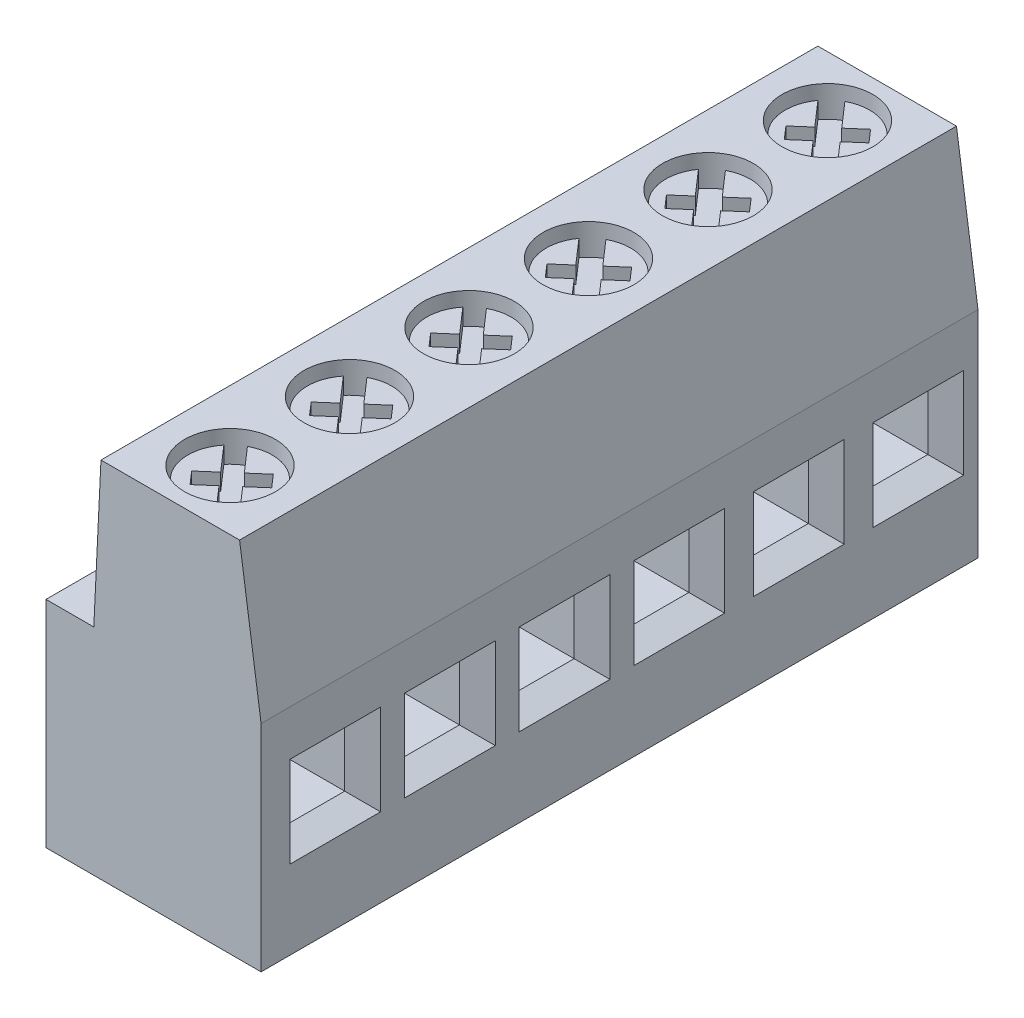
SolidWorks part; units mm, degrees
ref_plane "Front Plane" through (0, 0, 0) normal (0, 0, 1) x (1, 0, 0)
ref_plane "Top Plane" through (0, 0, 0) normal (0, 1, 0) x (1, 0, 0)
ref_plane "Right Plane" through (0, 0, 0) normal (1, 0, 0) x (0, 0, -1)
ref_plane "Plane1" through (0, 0, -15) normal (0, 0, -1) x (-1, 0, 0)
sketch "Sketch1" plane through (0, 0, -15) normal (0, 0, -1) x (-1, 0, 0)
  line L0 (-9, 0) -> (0, 0)
  line L1 (0, 0) -> (0, 15.2)
  line L2 (0, 15.2) -> (-8.1, 15.2)
  line L3 (-8.1, 15.2) -> (-9, 9)
  line L4 (-9, 9) -> (-9, 0)
extrude "Boss-Extrude1" add sketch "Sketch1" against normal blind 30
hole_wizard "Ø3.8 (3.8) Diameter Hole1" positions "Sketch3" profile "Sketch2" hole size "Ø3.8" standard "ANSI Metric"
sketch "Sketch3" plane through (0, 15.2, 0) normal (0, 1, 0) x (1, 0, 0)
  point P0 (5.2, 7.5)
sketch "Sketch2" plane through (5.2, 15.2, -7.5) normal (1, 0, 0) x (0, 0, 1)
  line L0 (0, 0) -> (0, 8)
  line L1 (0, 8) -> (1.9, 8)
  line L2 (1.9, 8) -> (1.9, 0)
  line L5 (1.9, 0) -> (0, 0)
  line L10 (0, 8) -> (-1.9, 8) construction
  line L11 (0, -6.35) -> (0, 107.95) construction
  dimension "Hole Dia." = 3.8
  dimension "Hole Depth" = 8
  dimension "Drill Angle" = 180
sketch "Sketch4" plane through (0, 7.2, 0) normal (0, 1, 0) x (-1, 0, 0)
  circle A0 centre (-5.2, -7.5) radius 1.766
extrude "Boss-Extrude2" add sketch "Sketch4" along normal blind 7.5
sketch "Sketch5" plane through (0, 14.7, 0) normal (0, 1, 0) x (-1, 0, 0)
  line L0 (-3.7681, -8.5335) -> (-6.029, -5.9407)
  arc A0 (-6.029, -5.9407) -> (-3.7681, -8.5335) centre (-5.2, -7.5) ccw
extrude "Cut-Extrude1" cut sketch "Sketch5" against normal blind 0.7
sketch "Sketch6" plane through (6.3675, 0, -5.5525) normal (0.7537, 0, -0.6572) x (-0.6572, 0, -0.7537)
  line L0 (2.5852, 14) -> (2.5852, 14.7)
  line L1 (2.5852, 14.7) -> (1.8852, 14.7)
  line L2 (1.8852, 14.7) -> (1.8852, 14)
  line L3 (1.8852, 14) -> (2.5852, 14)
extrude "Cut-Extrude2" cut sketch "Sketch6" against normal blind 0.8558
sketch "Sketch7" plane through (0, 14, 0) normal (0, 1, 0) x (-1, 0, 0)
  line L0 (-6.6319, -6.4665) -> (-4.371, -9.0593)
  arc A0 (-4.371, -9.0593) -> (-6.6319, -6.4665) centre (-5.2, -7.5) cw
extrude "Boss-Extrude3" add sketch "Sketch7" along normal blind 0.7
sketch "Sketch8" plane through (0, 14.7, 0) normal (0, 1, 0) x (-1, 0, 0)
  line L0 (-5.7315, -7.4991) -> (-6.3765, -8.0616)
  line L1 (-6.3765, -8.0616) -> (-5.9165, -8.5891)
  line L2 (-5.9165, -8.5891) -> (-5.2715, -8.0267)
  line L3 (-5.2715, -8.0267) -> (-5.7315, -7.4991)
extrude "Cut-Extrude3" cut sketch "Sketch8" against normal blind 0.7
hole_wizard "Ø3.8 (3.8) Diameter Hole2" positions "Sketch10" profile "Sketch9" hole size "Ø3.8" standard "ANSI Metric"
sketch "Sketch10" plane through (0, 15.2, 0) normal (0, 1, 0) x (1, 0, 0)
  point P0 (5.2, 2.5)
sketch "Sketch9" plane through (5.2, 15.2, -2.5) normal (1, 0, 0) x (0, 0, 1)
  line L0 (0, 0) -> (0, 8)
  line L1 (0, 8) -> (1.9, 8)
  line L2 (1.9, 8) -> (1.9, 0)
  line L5 (1.9, 0) -> (0, 0)
  line L10 (0, 8) -> (-1.9, 8) construction
  line L11 (0, -6.35) -> (0, 107.95) construction
  dimension "Hole Dia." = 3.8
  dimension "Hole Depth" = 8
  dimension "Drill Angle" = 180
sketch "Sketch11" plane through (0, 7.2, 0) normal (0, 1, 0) x (-1, 0, 0)
  circle A0 centre (-5.2, -2.5) radius 1.766
  dimension "D1" = 3.5319
extrude "Boss-Extrude4" add sketch "Sketch11" along normal blind 7.5
sketch "Sketch12" plane through (0, 14.7, 0) normal (0, 1, 0) x (-1, 0, 0)
  line L0 (-6.6319, -1.4665) -> (-4.371, -4.0593)
  arc A0 (-4.371, -4.0593) -> (-6.6319, -1.4665) centre (-5.2, -2.5) ccw
extrude "Cut-Extrude4" cut sketch "Sketch12" against normal blind 0.7
sketch "Sketch13" plane through (4.4938, 0, -3.9185) normal (-0.7537, 0, 0.6572) x (0.6572, 0, 0.7537)
  line L0 (1.8833, 14) -> (1.8833, 14.7)
  line L1 (1.8833, 14.7) -> (1.1833, 14.7)
  line L2 (1.1833, 14.7) -> (1.1833, 14)
  line L3 (1.1833, 14) -> (1.8833, 14)
extrude "Cut-Extrude5" cut sketch "Sketch13" against normal blind 0.8558
sketch "Sketch14" plane through (0, 14, 0) normal (0, 1, 0) x (-1, 0, 0)
  line L0 (-3.7681, -3.5335) -> (-6.029, -0.9407)
  arc A0 (-6.029, -0.9407) -> (-3.7681, -3.5335) centre (-5.2, -2.5) cw
extrude "Boss-Extrude5" add sketch "Sketch14" along normal blind 0.7
sketch "Sketch15" plane through (0, 14.7, 0) normal (0, 1, 0) x (-1, 0, 0)
  line L0 (-4.6685, -2.5009) -> (-4.0235, -1.9384)
  line L1 (-4.0235, -1.9384) -> (-4.4835, -1.4109)
  line L2 (-4.4835, -1.4109) -> (-5.1285, -1.9733)
  line L3 (-5.1285, -1.9733) -> (-4.6685, -2.5009)
extrude "Cut-Extrude6" cut sketch "Sketch15" against normal blind 0.7
hole_wizard "Ø3.8 (3.8) Diameter Hole3" positions "Sketch17" profile "Sketch16" hole size "Ø3.8" standard "ANSI Metric"
sketch "Sketch17" plane through (0, 15.2, 0) normal (0, 1, 0) x (1, 0, 0)
  point P0 (5.2, 12.5)
sketch "Sketch16" plane through (5.2, 15.2, -12.5) normal (1, 0, 0) x (0, 0, 1)
  line L0 (0, 0) -> (0, 8)
  line L1 (0, 8) -> (1.9, 8)
  line L2 (1.9, 8) -> (1.9, 0)
  line L5 (1.9, 0) -> (0, 0)
  line L10 (0, 8) -> (-1.9, 8) construction
  line L11 (0, -6.35) -> (0, 107.95) construction
  dimension "Hole Dia." = 3.8
  dimension "Hole Depth" = 8
  dimension "Drill Angle" = 180
sketch "Sketch18" plane through (0, 7.2, 0) normal (0, 1, 0) x (-1, 0, 0)
  circle A0 centre (-5.2, -12.5) radius 1.766
extrude "Boss-Extrude6" add sketch "Sketch18" along normal blind 7.5
sketch "Sketch19" plane through (0, 14.7, 0) normal (0, 1, 0) x (-1, 0, 0)
  line L0 (-3.7681, -13.5335) -> (-6.029, -10.9407)
  arc A0 (-6.029, -10.9407) -> (-3.7681, -13.5335) centre (-5.2, -12.5) ccw
extrude "Cut-Extrude7" cut sketch "Sketch19" against normal blind 0.7
sketch "Sketch20" plane through (8.8443, 0, -7.7122) normal (0.7537, 0, -0.6572) x (-0.6572, 0, -0.7537)
  line L0 (6.3537, 14) -> (6.3537, 14.7)
  line L1 (6.3537, 14.7) -> (5.6537, 14.7)
  line L2 (5.6537, 14.7) -> (5.6537, 14)
  line L3 (5.6537, 14) -> (6.3537, 14)
extrude "Cut-Extrude8" cut sketch "Sketch20" against normal blind 0.8558
sketch "Sketch21" plane through (0, 14, 0) normal (0, 1, 0) x (-1, 0, 0)
  line L0 (-6.6319, -11.4665) -> (-4.371, -14.0593)
  arc A0 (-4.371, -14.0593) -> (-6.6319, -11.4665) centre (-5.2, -12.5) cw
extrude "Boss-Extrude7" add sketch "Sketch21" along normal blind 0.7
sketch "Sketch22" plane through (0, 14.7, 0) normal (0, 1, 0) x (-1, 0, 0)
  line L0 (-5.7315, -12.4991) -> (-6.3765, -13.0616)
  line L1 (-6.3765, -13.0616) -> (-5.9165, -13.5891)
  line L2 (-5.9165, -13.5891) -> (-5.2715, -13.0267)
  line L3 (-5.2715, -13.0267) -> (-5.7315, -12.4991)
extrude "Cut-Extrude9" cut sketch "Sketch22" against normal blind 0.7
sketch "Sketch23" plane through (0, 0, 15) normal (0, 0, 1) x (1, 0, 0)
  line L0 (2.3, 9) -> (2.3, 15.2)
  line L1 (2.3, 15.2) -> (0, 15.2)
  line L2 (0, 15.2) -> (0, 9)
  line L3 (0, 9) -> (2.3, 9)
extrude "Cut-Extrude10" cut sketch "Sketch23" against normal through all
sketch "Sketch24" plane through (0, 0, 0) normal (0, -1, 0) x (1, 0, 0)
  line L0 (4.9, -12) -> (4.9, -13)
  line L1 (4.9, -13) -> (4.1, -13)
  line L2 (4.1, -13) -> (4.1, -12)
  line L3 (4.1, -12) -> (4.9, -12)
extrude "Boss-Extrude8" add sketch "Sketch24" along normal blind 3.5
sketch "Sketch25" plane through (0, 0, 0) normal (0, -1, 0) x (1, 0, 0)
  line L0 (4.9, -7) -> (4.9, -8)
  line L1 (4.9, -8) -> (4.1, -8)
  line L2 (4.1, -8) -> (4.1, -7)
  line L3 (4.1, -7) -> (4.9, -7)
extrude "Boss-Extrude9" add sketch "Sketch25" along normal blind 3.5
sketch "Sketch26" plane through (0, 0, 0) normal (0, -1, 0) x (1, 0, 0)
  line L0 (4.9, -2) -> (4.9, -3)
  line L1 (4.9, -3) -> (4.1, -3)
  line L2 (4.1, -3) -> (4.1, -2)
  line L3 (4.1, -2) -> (4.9, -2)
extrude "Boss-Extrude10" add sketch "Sketch26" along normal blind 3.5
sketch "Sketch27" plane through (9, 0, 0) normal (1, 0, 0) x (0, 0, -1)
  line L0 (13.9, 6.6) -> (11.1, 6.6)
  line L1 (11.1, 6.6) -> (11.1, 3.8)
  line L2 (11.1, 3.8) -> (13.9, 3.8)
  line L3 (13.9, 3.8) -> (13.9, 6.6)
extrude "Cut-Extrude11" cut sketch "Sketch27" against normal blind 8
sketch "Sketch28" plane through (9, 0, 0) normal (1, 0, 0) x (0, 0, -1)
  line L0 (8.9, 6.6) -> (6.1, 6.6)
  line L1 (6.1, 6.6) -> (6.1, 3.8)
  line L2 (6.1, 3.8) -> (8.9, 3.8)
  line L3 (8.9, 3.8) -> (8.9, 6.6)
extrude "Cut-Extrude12" cut sketch "Sketch28" against normal blind 8
sketch "Sketch29" plane through (9, 0, 0) normal (1, 0, 0) x (0, 0, -1)
  line L0 (3.9, 6.6) -> (1.1, 6.6)
  line L1 (1.1, 6.6) -> (1.1, 3.8)
  line L2 (1.1, 3.8) -> (3.9, 3.8)
  line L3 (3.9, 3.8) -> (3.9, 6.6)
extrude "Cut-Extrude13" cut sketch "Sketch29" against normal blind 8
draft "Draft1" type of draft neutral plane draft angle 2.77 faces to draft 1 face at (2.3, 12.1, 0) neutral plane through (0, 15.2, 15) neutral plane normal (0, 1, 0) parameters "D1"=2.77
chamfer "Chamfer1" distance 0.5 angle 63.435 1 edges at (9, 5.2, -8.9)
sketch "Sketch31" plane through (0, 0, 0) normal (0, -1, 0) x (1, 0, 0)
  line L0 (4.9, 3) -> (4.9, 2)
  line L1 (4.9, 2) -> (4.1, 2)
  line L2 (4.1, 2) -> (4.1, 3)
  line L3 (4.1, 3) -> (4.9, 3)
  line L4 (4.9, -3) -> (4.9, -2) construction
  line L5 (4.1, -2) -> (4.1, -3) construction
  dimension "D1" = 4
sketch "Sketch32" plane through (0, 0, 0) normal (0, -1, 0) x (1, 0, 0)
  line L0 (4.9, 7) -> (4.9, 6)
  line L1 (4.9, 6) -> (4.1, 6)
  line L2 (4.1, 6) -> (4.1, 7)
  line L3 (4.1, 7) -> (4.9, 7)
  line L4 (4.9, -3) -> (4.9, -2) construction
  line L5 (4.1, -2) -> (4.1, -3) construction
  dimension "D1" = 8
sketch "Sketch34" plane through (0, 0, 0) normal (0, -1, 0) x (1, 0, 0)
  line L0 (4.9, 11) -> (4.9, 10)
  line L1 (4.9, 10) -> (4.1, 10)
  line L2 (4.1, 10) -> (4.1, 11)
  line L3 (4.1, 11) -> (4.9, 11)
  line L4 (4.9, -3) -> (4.9, -2) construction
  line L5 (4.1, -2) -> (4.1, -3) construction
  dimension "D1" = 12
extrude "Boss-Extrude11" add sketch "Sketch31" along normal blind 3.5 contours L0 L1 L2 L3
extrude "Boss-Extrude12" add sketch "Sketch32" along normal blind 3.5 contours L0 L1 L2 L3
extrude "Boss-Extrude13" add sketch "Sketch34" along normal blind 3.5 contours L1 L2 L3 L0
sketch "Sketch35" plane through (9, 0, 0) normal (1, 0, 0) x (0, 0, -1)
  line L0 (-0.9, 6.6) -> (-3.7, 6.6)
  line L1 (-3.7, 6.6) -> (-3.7, 3.8)
  line L2 (-3.7, 3.8) -> (-0.9, 3.8)
  line L3 (-0.9, 3.8) -> (-0.9, 6.6)
  line L7 (1.1, 6.6) -> (1.1, 3.8) construction
  line L8 (1.1, 3.8) -> (3.9, 3.8) construction
  dimension "D1" = 2
extrude "Cut-Extrude14" cut sketch "Sketch35" against normal blind 8
sketch "Sketch36" plane through (9, 0, 0) normal (1, 0, 0) x (0, 0, -1)
  line L0 (-5.7, 6.6) -> (-8.5, 6.6)
  line L1 (-8.5, 6.6) -> (-8.5, 3.8)
  line L2 (-8.5, 3.8) -> (-5.7, 3.8)
  line L3 (-5.7, 3.8) -> (-5.7, 6.6)
  line L4 (-3.7, 3.8) -> (-0.9, 3.8) construction
  dimension "D1" = 2
  dimension "D2" = 2.8
extrude "Cut-Extrude15" cut sketch "Sketch36" against normal blind 8
sketch "Sketch37" plane through (9, 0, 0) normal (1, 0, 0) x (0, 0, -1)
  line L0 (-10.5, 6.6) -> (-13.3, 6.6)
  line L1 (-13.3, 6.6) -> (-13.3, 3.8)
  line L2 (-13.3, 3.8) -> (-10.5, 3.8)
  line L3 (-10.5, 3.8) -> (-10.5, 6.6)
  line L4 (-8.5, 6.6) -> (-8.5, 3.8) construction
  line L5 (-5.7, 6.6) -> (-8.5, 6.6) construction
  dimension "D1" = 2.8
  dimension "D2" = 2
extrude "Cut-Extrude16" cut sketch "Sketch37" against normal blind 8
chamfer "Chamfer2" distance 0.5 angle 63.435 12 edges at (9, 6.6, 11.9) (9, 5.2, 13.3) (9, 3.8, 11.9) (9, 5.2, 10.5) (9, 6.6, 7.1) (9, 5.2, 8.5) (9, 3.8, 7.1) (9, 5.2, 5.7) (9, 6.6, 2.3) (9, 5.2, 3.7) (9, 3.8, 2.3) (9, 5.2, 0.9)
hole_wizard "Ø3.8 (3.8) Diameter Hole4" positions "Sketch38" profile "Sketch39" hole size "Ø3.8" standard "ANSI Metric"
sketch "Sketch38" plane through (0, 15.2, 0) normal (0, 1, 0) x (1, 0, 0)
  point P0 (5.2, -2.5)
  dimension "D1" = 5
sketch "Sketch39" plane through (5.2, 15.2, 2.5) normal (1, 0, 0) x (0, 0, 1)
  line L0 (0, 0) -> (0, 8)
  line L1 (0, 8) -> (1.9, 8)
  line L2 (1.9, 8) -> (1.9, 0)
  line L5 (1.9, 0) -> (0, 0)
  line L10 (0, 8) -> (-1.9, 8) construction
  line L11 (0, -6.35) -> (0, 107.95) construction
  dimension "Hole Dia." = 3.8
  dimension "Hole Depth" = 8
  dimension "Drill Angle" = 180
hole_wizard "Ø3.8 (3.8) Diameter Hole5" positions "Sketch40" profile "Sketch41" hole size "Ø3.8" standard "ANSI Metric"
sketch "Sketch40" plane through (0, 15.2, 0) normal (0, 1, 0) x (1, 0, 0)
  point P0 (5.2, -7.5)
  dimension "D1" = 5
sketch "Sketch41" plane through (5.2, 15.2, 7.5) normal (1, 0, 0) x (0, 0, 1)
  line L0 (0, 0) -> (0, 8)
  line L1 (0, 8) -> (1.9, 8)
  line L2 (1.9, 8) -> (1.9, 0)
  line L5 (1.9, 0) -> (0, 0)
  line L10 (0, 8) -> (-1.9, 8) construction
  line L11 (0, -6.35) -> (0, 107.95) construction
  dimension "Hole Dia." = 3.8
  dimension "Hole Depth" = 8
  dimension "Drill Angle" = 180
hole_wizard "Ø3.8 (3.8) Diameter Hole6" positions "Sketch42" profile "Sketch43" hole size "Ø3.8" standard "ANSI Metric"
sketch "Sketch42" plane through (0, 15.2, 0) normal (0, 1, 0) x (1, 0, 0)
  point P0 (5.2, -12.5)
  dimension "D1" = 5
sketch "Sketch43" plane through (5.2, 15.2, 12.5) normal (1, 0, 0) x (0, 0, 1)
  line L0 (0, 0) -> (0, 8)
  line L1 (0, 8) -> (1.9, 8)
  line L2 (1.9, 8) -> (1.9, 0)
  line L5 (1.9, 0) -> (0, 0)
  line L10 (0, 8) -> (-1.9, 8) construction
  line L11 (0, -6.35) -> (0, 107.95) construction
  dimension "Hole Dia." = 3.8
  dimension "Hole Depth" = 8
  dimension "Drill Angle" = 180
sketch "Sketch74" plane through (0, 7.2, 0) normal (0, 1, 0) x (1, 0, 0)
  circle A0 centre (5.2, -2.5) radius 1.765
  dimension "D1" = 3.53
extrude "Boss-Extrude20" add sketch "Sketch74" along normal blind 7.5 separate body
sketch "Sketch75" plane through (0, 7.2, 0) normal (0, 1, 0) x (1, 0, 0)
  circle A0 centre (5.2, -7.5) radius 1.765
  dimension "D1" = 3.53
extrude "Boss-Extrude21" add sketch "Sketch75" along normal blind 7.5
sketch "Sketch76" plane through (0, 7.2, 0) normal (0, 1, 0) x (1, 0, 0)
  circle A0 centre (5.2, -12.5) radius 1.765
  dimension "D1" = 3.53
extrude "Boss-Extrude22" add sketch "Sketch76" along normal blind 7.5
sketch "Sketch77" plane through (0, 14.7, 0) normal (0, 1, 0) x (1, 0, 0)
  line L0 (5.2714, -1.9733) -> (4.371, -0.9407)
  line L1 (5.2027, -2.9619) -> (6.1157, -4.0089)
  line L2 (4.7427, -2.4343) -> (3.8298, -1.3874)
  line L3 (5.7315, -2.5009) -> (6.6319, -3.5335)
  line L4 (5.2714, -1.9733) -> (5.9196, -1.4081)
  line L5 (5.9196, -1.4081) -> (6.3796, -1.9357)
  line L6 (6.3796, -1.9357) -> (5.7315, -2.5009)
  line L7 (4.7427, -2.4343) -> (4.0945, -2.9995)
  line L8 (4.0945, -2.9995) -> (4.5546, -3.5271)
  line L9 (4.5546, -3.5271) -> (5.2027, -2.9619)
  arc A0 (4.371, -0.9407) -> (6.6319, -3.5335) centre (5.2, -2.5) cw
  arc A1 (6.1157, -4.0089) -> (3.8298, -1.3874) centre (5.2, -2.5) cw
  circle A2 centre (5.2, -2.5) radius 1.765 construction
  arc A3 (3.8298, -1.3874) -> (4.3717, -0.9414) centre (5.2, -2.5) cw
  arc A4 (6.1157, -4.0089) -> (6.6355, -3.527) centre (5.2, -2.5) ccw
  circle M1 centre (5.2, -2.5) radius 1.765
  dimension "D1" = 1.37
  dimension "D2" = 0.7
  dimension "D3" = 0.86
extrude "Cut-Extrude27" cut sketch "Sketch77" against normal blind 0.7 contours L8 L9 L1 L3 L6 L5 L4 L0 L2 L7 M1
sketch "Sketch79" plane through (0, 14.7, 0) normal (0, 1, 0) x (1, 0, 0)
  line L0 (5.2714, -6.9733) -> (4.371, -5.9407)
  line L1 (5.2027, -7.9619) -> (6.1157, -9.0089)
  line L2 (4.7427, -7.4343) -> (3.8298, -6.3874)
  line L3 (5.7315, -7.5009) -> (6.6319, -8.5335)
  line L4 (5.2714, -6.9733) -> (5.9196, -6.4081)
  line L5 (5.9196, -6.4081) -> (6.3796, -6.9357)
  line L6 (6.3796, -6.9357) -> (5.7315, -7.5009)
  line L7 (4.7427, -7.4343) -> (4.0945, -7.9995)
  line L8 (4.0945, -7.9995) -> (4.5546, -8.5271)
  line L9 (4.5546, -8.5271) -> (5.2027, -7.9619)
  arc A0 (4.371, -5.9407) -> (6.6319, -8.5335) centre (5.2, -7.5) cw
  arc A1 (6.1157, -9.0089) -> (3.8298, -6.3874) centre (5.2, -7.5) cw
  arc A3 (3.8298, -6.3874) -> (4.3717, -5.9414) centre (5.2, -7.5) cw
  arc A4 (6.1157, -9.0089) -> (6.6355, -8.527) centre (5.2, -7.5) ccw
  circle M32 centre (5.2, -7.5) radius 1.765
  dimension "D1" = 1.37
  dimension "D2" = 0.7
  dimension "D3" = 0.86
sketch "Sketch80" plane through (0, 14.7, 0) normal (0, 1, 0) x (1, 0, 0)
  line L0 (5.2714, -11.9733) -> (4.371, -10.9407)
  line L1 (5.2027, -12.9619) -> (6.1157, -14.0089)
  line L2 (4.7427, -12.4343) -> (3.8298, -11.3874)
  line L3 (5.7315, -12.5009) -> (6.6319, -13.5335)
  line L4 (5.2714, -11.9733) -> (5.9196, -11.4081)
  line L5 (5.9196, -11.4081) -> (6.3796, -11.9357)
  line L6 (6.3796, -11.9357) -> (5.7315, -12.5009)
  line L7 (4.7427, -12.4343) -> (4.0945, -12.9995)
  line L8 (4.0945, -12.9995) -> (4.5546, -13.5271)
  line L9 (4.5546, -13.5271) -> (5.2027, -12.9619)
  arc A0 (4.371, -10.9407) -> (6.6319, -13.5335) centre (5.2, -12.5) cw
  arc A1 (6.1157, -14.0089) -> (3.8298, -11.3874) centre (5.2, -12.5) cw
  arc A3 (3.8298, -11.3874) -> (4.3717, -10.9414) centre (5.2, -12.5) cw
  arc A4 (6.1157, -14.0089) -> (6.6355, -13.527) centre (5.2, -12.5) ccw
  circle M32 centre (5.2, -12.5) radius 1.765
  dimension "D1" = 1.37
  dimension "D2" = 0.7
  dimension "D3" = 0.86
extrude "Cut-Extrude28" cut sketch "Sketch79" against normal blind 0.7 contours L8 L9 L1 L3 L6 L5 L4 L0 L2 L7 M32
extrude "Cut-Extrude29" cut sketch "Sketch80" against normal blind 0.7 contours L8 L9 L1 L3 L6 L5 L4 L0 L2 L7 M32
